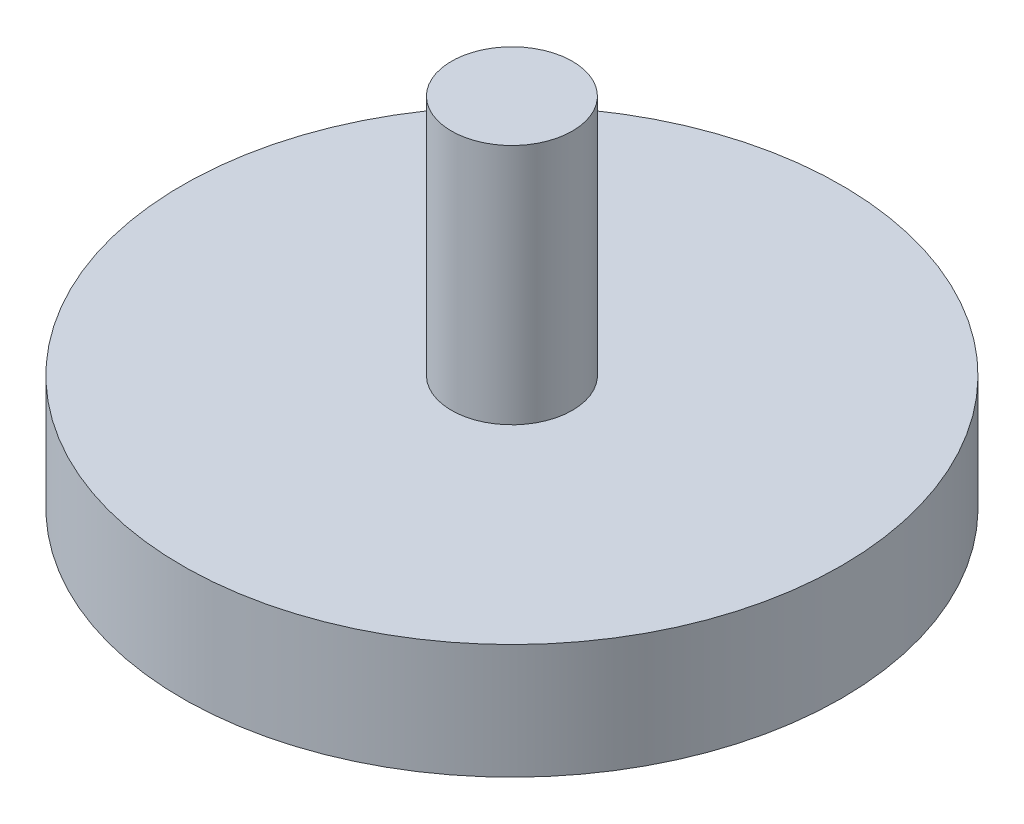
SolidWorks part; units mm, degrees
material "Acciaio al carbonio semplice"
ref_plane "Piano frontale" through (0, 0, 0) normal (0, 0, 1) x (1, 0, 0)
ref_plane "Piano superiore" through (0, 0, 0) normal (0, 1, 0) x (1, 0, 0)
ref_plane "Piano destro" through (0, 0, 0) normal (1, 0, 0) x (0, 0, -1)
sketch "Schizzo1" plane through (0, 0, 0) normal (0, 0, 1) x (1, 0, 0)
  line L1 (20, 68) -> (109, 68)
  line L2 (0, 0) -> (48, 0)
  line L3 (48, 0) -> (48, 5)
  line L4 (48, 5) -> (30, 5)
  line L5 (30, 5) -> (30, 30)
  line L6 (30, 30) -> (109, 30)
  line L7 (109, 30) -> (109, 68)
  line L8 (0, 0) -> (0, 148)
  line L9 (0, 148) -> (20, 148)
  line L10 (20, 148) -> (20, 68)
  line L11 (0, -1000) -> (0, 49000) construction
  point P1 (30, 17.5)
  dimension "D1" = 25
  dimension "D2" = 5
  dimension "D3" = 38
  dimension "D4" = 109
  dimension "D5" = 48
  dimension "D6" = 20
  dimension "D7" = 30
  dimension "D8" = 80
revolve "Rivoluzione1" add sketch "Schizzo1" angle 360 about L11
sketch "Schizzo3" plane through (0, 30, 0) normal (0, -1, 0) x (1, 0, 0)
  line L0 (0, -1000) -> (0, 49000) construction
  line L2 (-7.5, 45) -> (7.5, 45)
  line L3 (-7.5, 45) -> (-7.5, 0)
  line L4 (-7.5, 0) -> (7.5, 0)
  line L5 (7.5, 45) -> (7.5, 0)
  line L6 (-7.5, 45) -> (7.5, 0) construction
  line L7 (-7.5, 0) -> (7.5, 45) construction
  point P1 (0, 22.5)
  dimension "D1" = 15
  dimension "D2" = 45
extrude "Estrusione-Estrusione1" add sketch "Schizzo3" along normal up to surface (25 mm away) up to face at (30, 5, 0)
sketch "Schizzo4" plane through (0, 0, 0) normal (0, 0, 1) x (1, 0, 0)
  line L0 (0, 0) -> (0, 148) construction
  line L1 (20, 148) -> (-20, 148) construction
